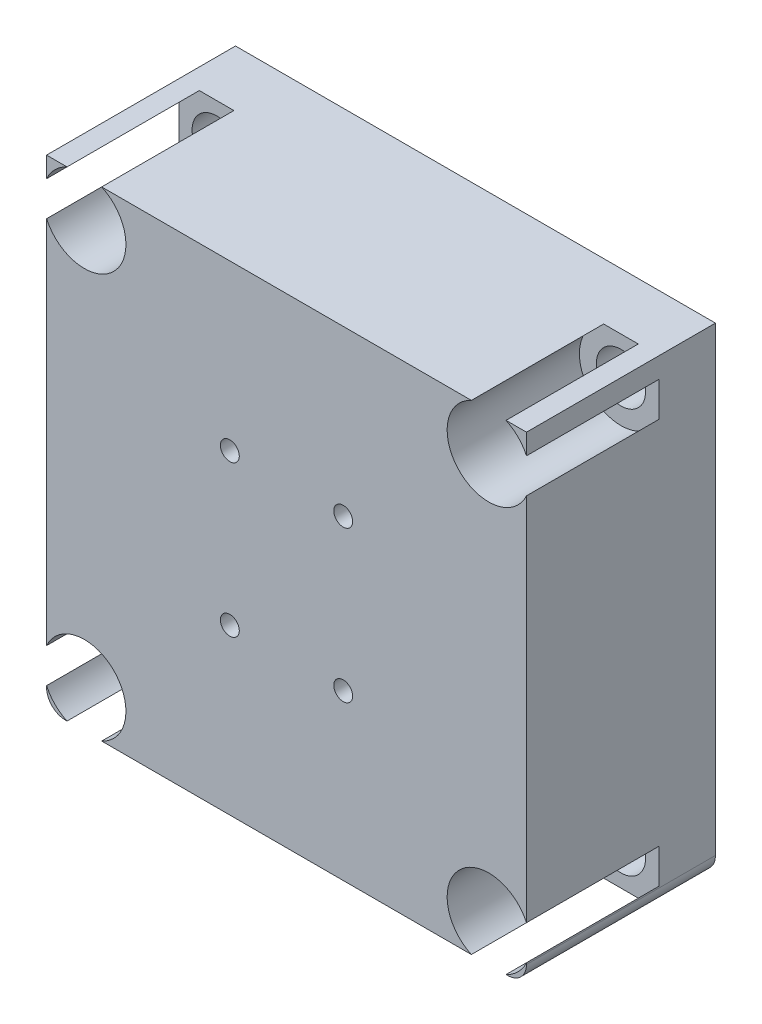
SolidWorks part; units mm, degrees
ref_plane "Front Plane" through (0, 0, 0) normal (0, 0, 1) x (1, 0, 0)
ref_plane "Top Plane" through (0, 0, 0) normal (0, 1, 0) x (1, 0, 0)
ref_plane "Right Plane" through (0, 0, 0) normal (1, 0, 0) x (0, 0, -1)
sketch "Sketch1" plane through (0, 0, 0) normal (0, 0, 1) x (1, 0, 0)
  line L8 (-12.7, 12.7) -> (-12.7, -11.7)
  line L9 (-11.7, -12.7) -> (11.7, -12.7)
  line L10 (12.7, -11.7) -> (12.7, 12.7)
  line L11 (12.7, 12.7) -> (-12.7, 12.7)
  line L12 (-12.7, 12.7) -> (-12.7, -11.7)
  line L13 (-11.7, -12.7) -> (11.7, -12.7)
  line L14 (12.7, -11.7) -> (12.7, 12.7)
  line L15 (12.7, 12.7) -> (-12.7, 12.7)
  arc A4 (-12.7, -11.7) -> (-11.7, -12.7) centre (-11.7, -11.7) ccw
  arc A5 (11.7, -12.7) -> (12.7, -11.7) centre (11.7, -11.7) ccw
  arc A6 (-12.7, -11.7) -> (-11.7, -12.7) centre (-11.7, -11.7) ccw
  arc A7 (11.7, -12.7) -> (12.7, -11.7) centre (11.7, -11.7) ccw
  dimension "D1" = 0
extrude "Boss-Extrude1" add sketch "Sketch1" along normal blind 10
sketch "Sketch2" plane through (0, 0, 10) normal (0, 0, 1) x (1, 0, 0)
  line L1 (-3, 4) -> (3, 4)
  line L2 (-3, 4) -> (-3, -4)
  line L3 (-3, -4) -> (3, -4)
  line L4 (3, 4) -> (3, -4)
  line L5 (-3, 4) -> (3, -4) construction
  line L6 (-3, -4) -> (3, 4) construction
  point P0 (0, 0)
  dimension "D1" = 6
  dimension "D2" = 8
  dimension "D3" = 0
hole_wizard "Ø1.0mm Dowel Hole1" positions "Sketch3" profile "Sketch4" hole size "Ø1.0" standard "ANSI Metric" end condition through all
sketch "Sketch3" plane through (0, 0, 10) normal (0, 0, 1) x (1, 0, 0)
  point P0 (3, -4)
  point P3 (-3, -4)
  point P6 (-3, 4)
  point P9 (3, 4)
sketch "Sketch4" plane through (3, -4, 10) normal (1, 0, 0) x (0, -1, 0)
  line L0 (0, 0) -> (0, 10)
  line L1 (0, 10) -> (0.5, 10)
  line L2 (0.5, 10) -> (0.5, 0)
  line L5 (0.5, 0) -> (0, 0)
  line L11 (0, -6.35) -> (0, 107.95) construction
  dimension "Thru Hole Dia." = 1
  dimension "Thru Hole Depth" = 10
hole_wizard "CBORE for M2 SHCS1" positions "Sketch5" profile "Sketch6" counterbore size "M2" standard "ANSI Metric" end condition through all
sketch "Sketch5" plane through (0, 0, 10) normal (0, 0, 1) x (1, 0, 0)
  point P0 (10.7, -10.7)
  point P3 (-10.7, -10.7)
  point P6 (-10.7, 10.7)
  point P9 (10.7, 10.7)
sketch "Sketch6" plane through (10.7, -10.7, 10) normal (1, 0, 0) x (0, -1, 0)
  line L0 (0, 0) -> (0, 10)
  line L1 (0, 10) -> (1.3, 10)
  line L3 (1.3, 10) -> (1.3, 7)
  line L4 (1.3, 7) -> (2.2, 7)
  line L5 (2.2, 7) -> (2.2, 0)
  line L7 (2.2, 0) -> (0, 0)
  line L11 (0, -6.35) -> (0, 107.95) construction
  dimension "Thru Hole Dia." = 2.6
  dimension "Thru Hole Depth" = 10
  dimension "C'Bore Dia." = 4.4
  dimension "C'Bore Depth" = 7
